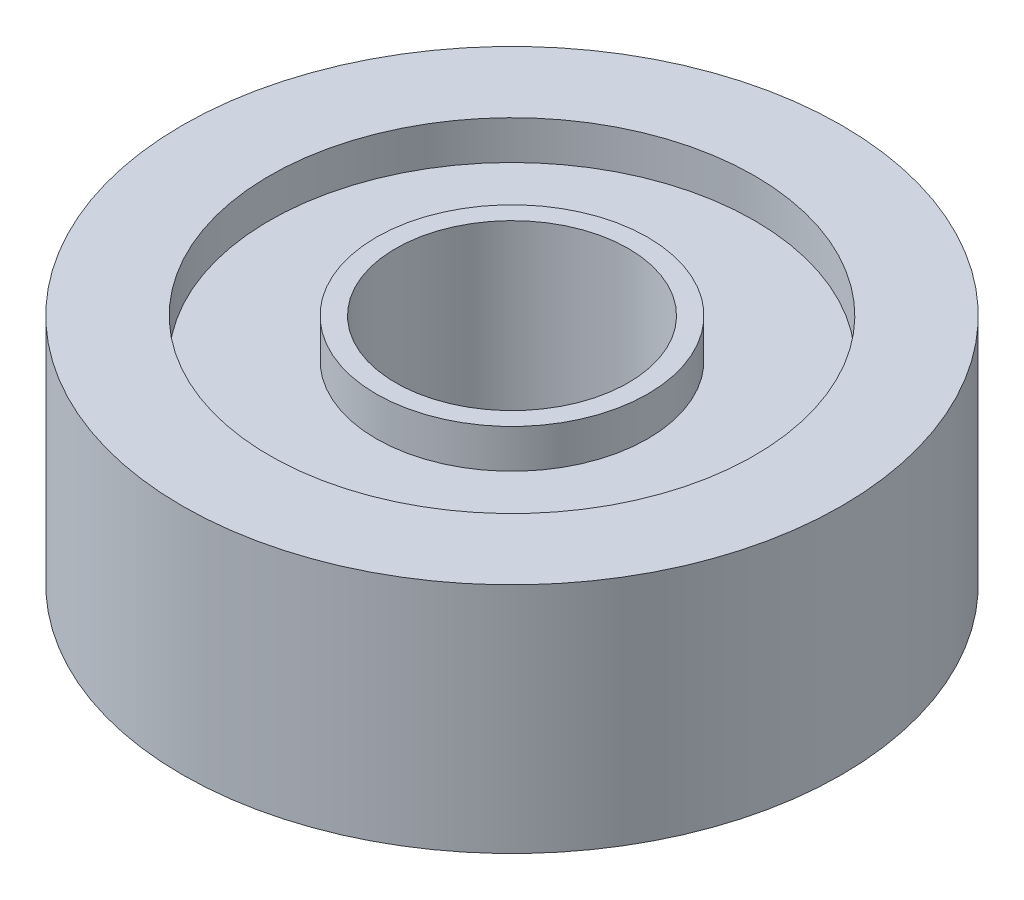
SolidWorks part; units mm, degrees
material "ABS"
ref_plane "Front Plane" through (0, 0, 0) normal (0, 0, 1) x (1, 0, 0)
ref_plane "Top Plane" through (0, 0, 0) normal (0, 1, 0) x (1, 0, 0)
ref_plane "Right Plane" through (0, 0, 0) normal (1, 0, 0) x (0, 0, -1)
sketch "Sketch1" plane through (0, 0, 0) normal (0, 0, 1) x (1, 0, 0)
  line L0 (0, 0) -> (0, 3.6484) construction
  line L1 (-3, 0) -> (-3, 6)
  line L2 (-3, 6) -> (-3.5, 6)
  line L3 (-3.5, 6) -> (-3.5, 5)
  line L4 (-3.5, 5) -> (-6.25, 5)
  line L5 (-6.25, 5) -> (-6.25, 6)
  line L6 (-6.25, 6) -> (-8.5, 6)
  line L7 (-8.5, 6) -> (-8.5, 0)
  line L8 (-8.5, 0) -> (-3, 0)
  dimension "D1" = 1
  dimension "D2" = 6
  dimension "D3" = 17
  dimension "D4" = 12.5
  dimension "D5" = 7
  dimension "D6" = 6
revolve "Revolve1" add sketch "Sketch1" angle 360 about L0
